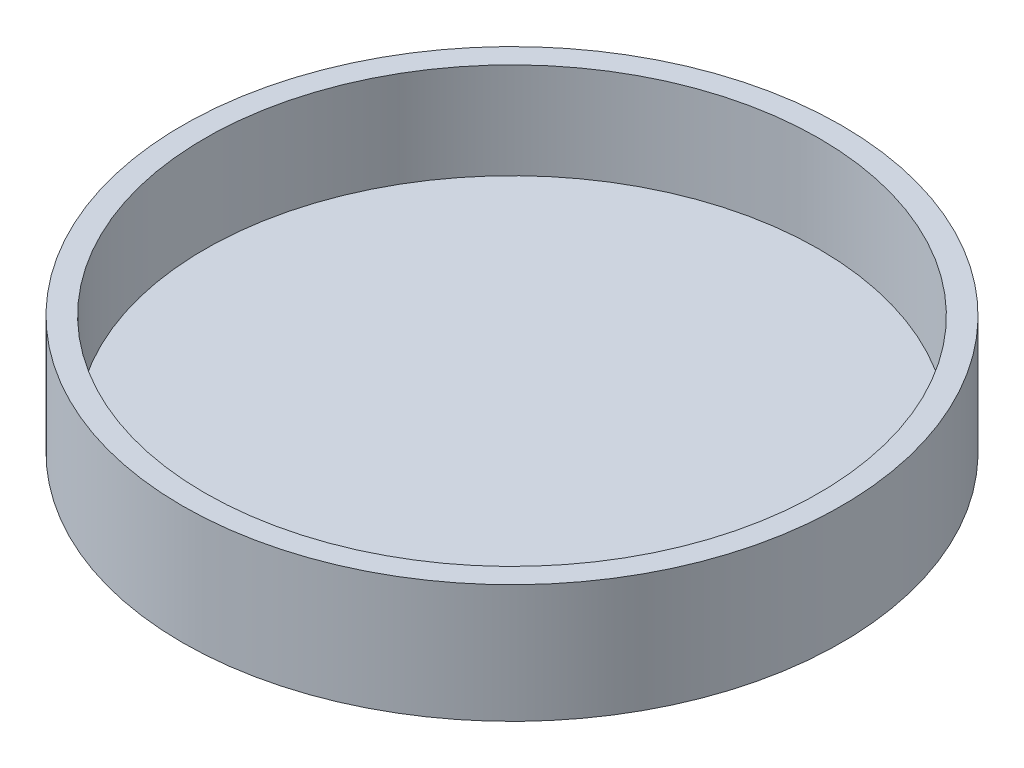
SolidWorks part; units mm, degrees
ref_plane "Front Plane" through (0, 0, 0) normal (0, 0, 1) x (1, 0, 0)
ref_plane "Top Plane" through (0, 0, 0) normal (0, 1, 0) x (1, 0, 0)
ref_plane "Right Plane" through (0, 0, 0) normal (1, 0, 0) x (0, 0, -1)
other "Configuration Table"
sketch "Sketch1" plane through (0, 0, 0) normal (0, 1, 0) x (1, 0, 0)
  circle A0 centre (0, 0) radius 51.5
extrude "YUVA_1L_halka_1" add sketch "Sketch1" along normal blind 18.5 from offset 6.5 separate body
sketch "Sketch2" plane through (0, 0, 0) normal (0, 1, 0) x (1, 0, 0)
  circle A0 centre (0, 0) radius 48
extrude "YUVA_1L_halka_2" cut sketch "Sketch2" along normal blind 16 from offset 10
